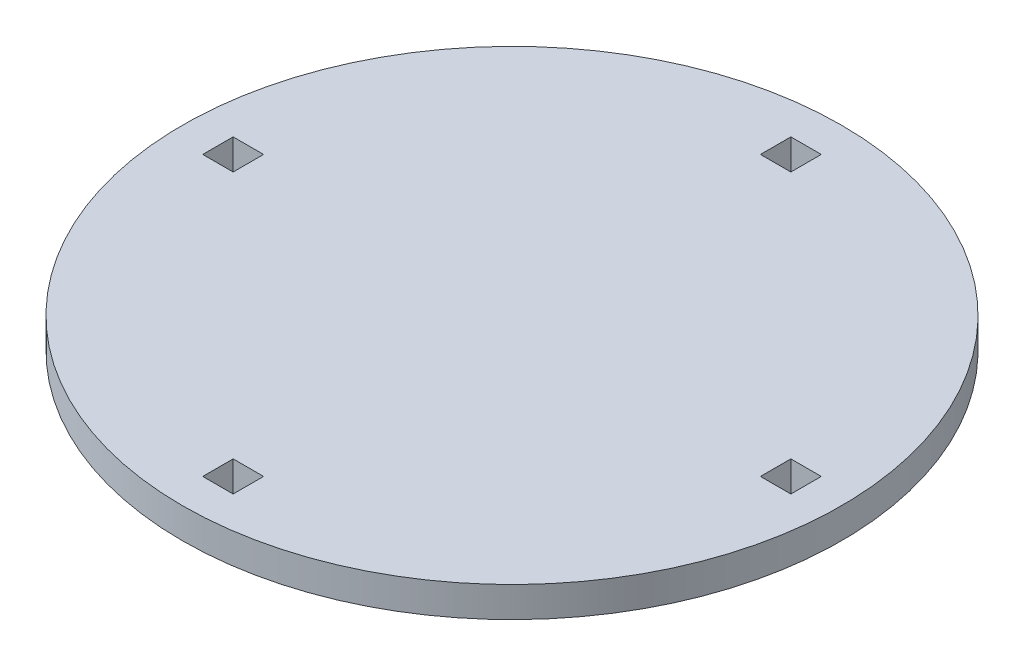
SolidWorks part; units mm, degrees
ref_plane "Front Plane" through (0, 0, 0) normal (0, 0, 1) x (1, 0, 0)
ref_plane "Top Plane" through (0, 0, 0) normal (0, 1, 0) x (1, 0, 0)
ref_plane "Right Plane" through (0, 0, 0) normal (1, 0, 0) x (0, 0, -1)
sketch "Sketch1" plane through (0, 0, 0) normal (0, 1, 0) x (1, 0, 0)
  circle A0 centre (0, 0) radius 32.5
  dimension "D1" = 65
extrude "Boss-Extrude1" add sketch "Sketch1" along normal blind 3
sketch "Sketch2" plane through (0, 0, 0) normal (0, 1, 0) x (1, 0, 0)
  line L1 (-24.25, -13.25) -> (24.25, -13.25)
  line L2 (-24.25, -13.25) -> (-24.25, 13.25)
  line L3 (-24.25, 13.25) -> (24.25, 13.25)
  line L4 (24.25, -13.25) -> (24.25, 13.25)
  line L5 (-24.25, -13.25) -> (24.25, 13.25) construction
  line L6 (-24.25, 13.25) -> (24.25, -13.25) construction
  point P0 (0, 0)
  dimension "D1" = 48.5
  dimension "D2" = 26.5
sketch "Sketch3" plane through (0, 0, 0) normal (0, 1, 0) x (1, 0, 0)
  line L0 (26, 1.5) -> (29, 1.5)
  line L1 (-1.5, 26) -> (1.5, 26)
  line L2 (-1.5, 26) -> (-1.5, 29)
  line L3 (-1.5, 29) -> (1.5, 29)
  line L4 (1.5, 26) -> (1.5, 29)
  line L5 (-1.5, 26) -> (1.5, 29) construction
  line L6 (-1.5, 29) -> (1.5, 26) construction
  line L7 (29, 1.5) -> (29, -1.5)
  line L8 (26, 1.5) -> (26, -1.5)
  line L9 (26, -1.5) -> (29, -1.5)
  line L10 (1.5, -26) -> (1.5, -29)
  line L11 (1.5, -29) -> (-1.5, -29)
  line L12 (1.5, -26) -> (-1.5, -26)
  line L13 (-1.5, -26) -> (-1.5, -29)
  line L14 (-26, -1.5) -> (-29, -1.5)
  line L15 (-29, -1.5) -> (-29, 1.5)
  line L16 (-26, -1.5) -> (-26, 1.5)
  line L17 (-26, 1.5) -> (-29, 1.5)
  circle A0 centre (0, 0) radius 27.5 construction
  point P3 (0, 27.5)
  point P23 (0, 0)
  dimension "D1" = 55
  dimension "D2" = 3
  dimension "D3" = 3
  dimension "D4" = 4
extrude "Cut-Extrude4" cut sketch "Sketch3" along normal blind 10
